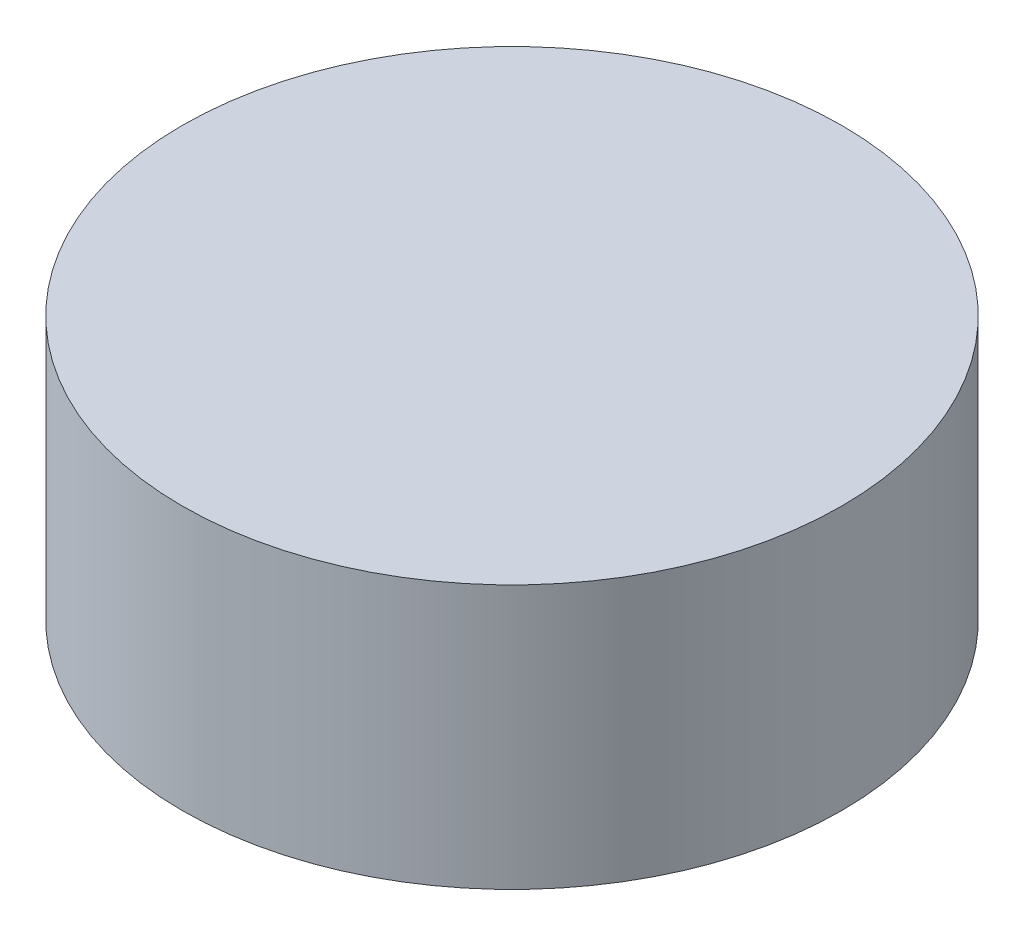
SolidWorks part; units mm, degrees
ref_plane "Alzado" through (0, 0, 0) normal (0, 0, 1) x (1, 0, 0)
ref_plane "Planta" through (0, 0, 0) normal (0, 1, 0) x (1, 0, 0)
ref_plane "Vista lateral" through (0, 0, 0) normal (1, 0, 0) x (0, 0, -1)
sketch "Croquis1" plane through (0, 0, 0) normal (0, 1, 0) x (1, 0, 0)
  circle A0 centre (0, 0) radius 25
  dimension "D1" = 50
extrude "Saliente-Extruir1" add sketch "Croquis1" along normal blind 20
